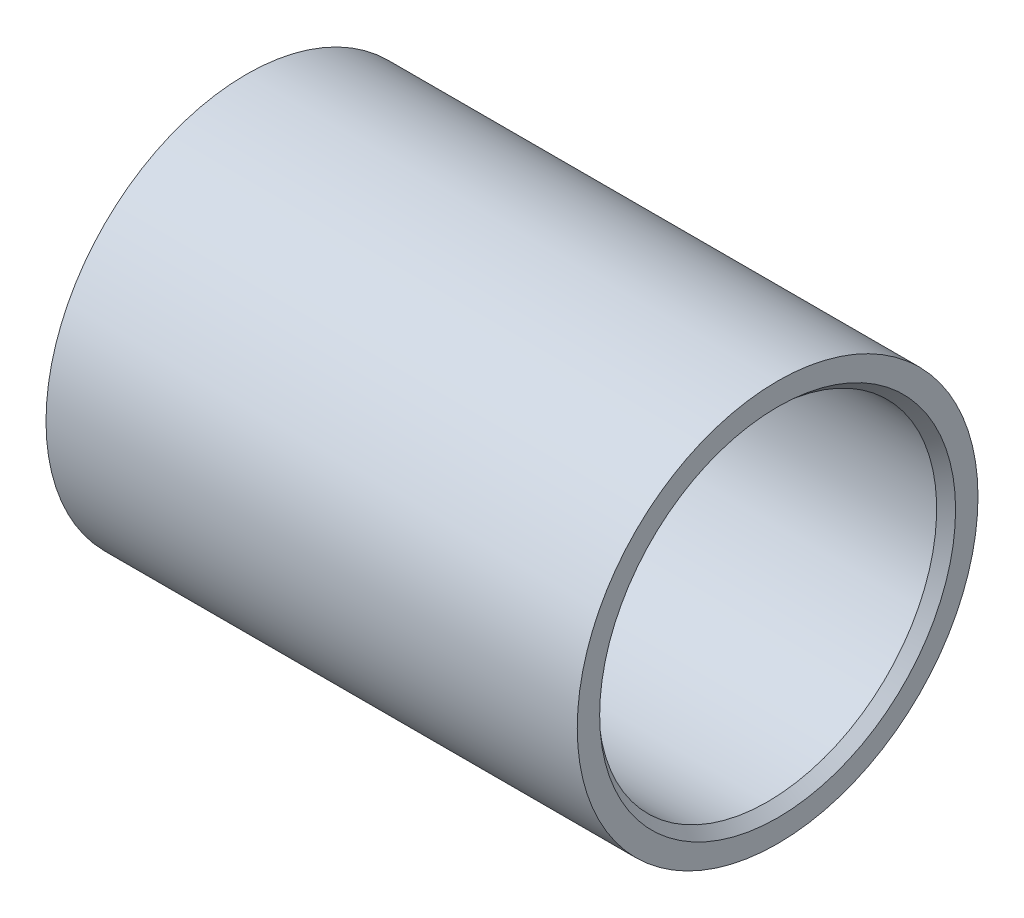
SolidWorks part; units mm, degrees
ref_plane "Front Plane" through (0, 0, 0) normal (0, 0, 1) x (1, 0, 0)
ref_plane "Top Plane" through (0, 0, 0) normal (0, 1, 0) x (1, 0, 0)
ref_plane "Right Plane" through (0, 0, 0) normal (1, 0, 0) x (0, 0, -1)
sketch "Sketch1" plane through (0, 0, 0) normal (0, 0, 1) x (1, 0, 0)
  line L0 (-18.6685, 13.5027) -> (-17.904, 12.7381)
  line L1 (-17.904, 12.7381) -> (20.5695, 12.7381)
  line L2 (20.5695, 12.7381) -> (21.3315, 13.3994)
  line L3 (21.3315, 13.3994) -> (21.3315, 15.0876)
  line L4 (21.3315, 15.0876) -> (-18.6685, 15.0876)
  line L5 (-18.6685, 15.0876) -> (-18.6685, 13.5027)
  line L6 (-18.6685, 0) -> (21.3315, 0) construction
revolve "Revolve1" add sketch "Sketch1" angle 360 about L6
